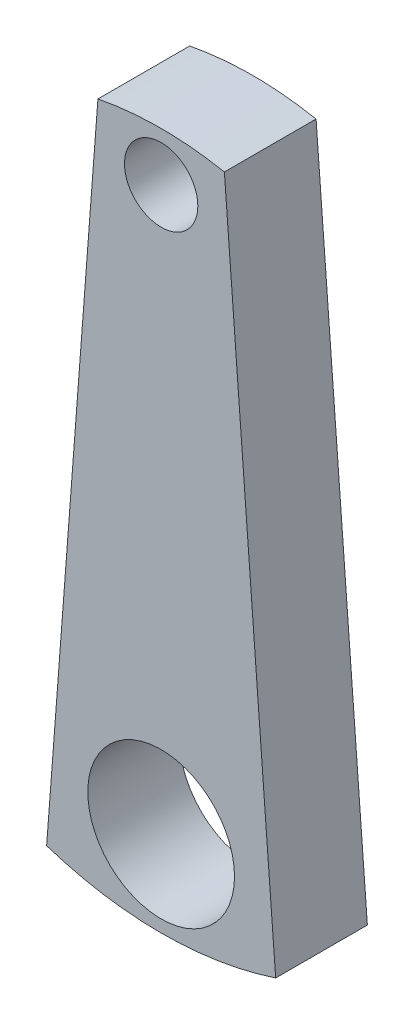
SolidWorks part; units mm, degrees
ref_plane "Front Plane" through (0, 0, 0) normal (0, 0, 1) x (1, 0, 0)
ref_plane "Top Plane" through (0, 0, 0) normal (0, 1, 0) x (1, 0, 0)
ref_plane "Right Plane" through (0, 0, 0) normal (1, 0, 0) x (0, 0, -1)
sketch "Sketch1" plane through (0, 0, 0) normal (0, 0, 1) x (1, 0, 0)
  line L3 (-10.3441, 53) -> (-18.735, -57)
  line L4 (10.3441, 53) -> (18.735, -57)
  circle A1 centre (0, 46) radius 6
  circle A2 centre (0, -46) radius 12
  arc A4 (10.3441, 53) -> (-10.3441, 53) centre (0, 0) ccw
  arc A5 (-18.735, -57) -> (18.735, -57) centre (0, 0) ccw
  dimension "D1" = 46
  dimension "D3" = 12
  dimension "D4" = 24
  dimension "D2" = 46
extrude "Boss-Extrude1" add sketch "Sketch1" along normal blind 15
